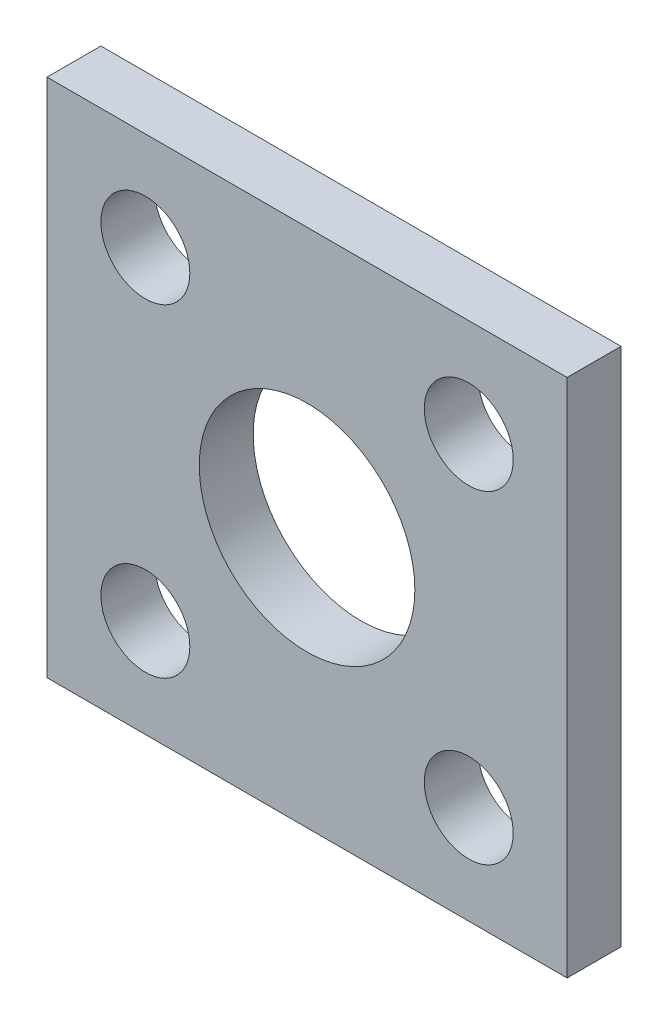
SolidWorks part; units mm, degrees
material "Acrylic (Medium-high impact)"
ref_plane "Front Plane" through (0, 0, 0) normal (0, 0, 1) x (1, 0, 0)
ref_plane "Top Plane" through (0, 0, 0) normal (0, 1, 0) x (1, 0, 0)
ref_plane "Right Plane" through (0, 0, 0) normal (1, 0, 0) x (0, 0, -1)
sketch "Sketch1" plane through (0, 0, 0) normal (0, 0, 1) x (1, 0, 0)
  line L0 (39.125, 39.125) -> (9.125, 9.125) construction
  line L1 (0, 0) -> (48.25, 0)
  line L2 (0, 0) -> (0, 48.25)
  line L3 (0, 48.25) -> (48.25, 48.25)
  line L4 (48.25, 0) -> (48.25, 48.25)
  line L5 (9.125, 9.125) -> (39.125, 9.125) construction
  line L6 (9.125, 9.125) -> (9.125, 39.125) construction
  line L7 (9.125, 39.125) -> (39.125, 39.125) construction
  line L8 (39.125, 9.125) -> (39.125, 39.125) construction
  line L9 (5, 9.125) -> (0, 9.125) construction
  line L10 (34.8959, 1.8) -> (30.6668, 9.125)
  line L11 (17.5832, 9.125) -> (13.3541, 16.45)
  line L12 (13.3541, 16.45) -> (4.8959, 16.45)
  line L13 (4.8959, 16.45) -> (0.6668, 9.125)
  line L14 (0.6668, 9.125) -> (4.8959, 1.8)
  line L15 (4.8959, 1.8) -> (13.3541, 1.8)
  line L16 (13.3541, 1.8) -> (17.5832, 9.125)
  line L17 (43.3541, 1.8) -> (34.8959, 1.8)
  line L18 (47.5832, 9.125) -> (43.3541, 1.8)
  line L19 (43.3541, 16.45) -> (47.5832, 9.125)
  line L20 (9.125, 24.125) -> (0, 24.125) construction
  line L21 (24.125, 9.125) -> (24.125, 0) construction
  line L22 (34.8959, 16.45) -> (43.3541, 16.45)
  line L23 (30.6668, 9.125) -> (34.8959, 16.45)
  line L24 (43.3541, 31.8) -> (47.5832, 39.125)
  line L25 (47.5832, 39.125) -> (43.3541, 46.45)
  line L26 (43.3541, 46.45) -> (34.8959, 46.45)
  line L27 (34.8959, 46.45) -> (30.6668, 39.125)
  line L28 (30.6668, 39.125) -> (34.8959, 31.8)
  line L29 (34.8959, 31.8) -> (43.3541, 31.8)
  line L30 (4.8959, 31.8) -> (0.6668, 39.125)
  line L31 (0.6668, 39.125) -> (4.8959, 46.45)
  line L32 (4.8959, 46.45) -> (13.3541, 46.45)
  line L33 (13.3541, 46.45) -> (17.5832, 39.125)
  line L34 (17.5832, 39.125) -> (13.3541, 31.8)
  line L35 (13.3541, 31.8) -> (4.8959, 31.8)
  circle A0 centre (9.125, 9.125) radius 4.125
  circle A1 centre (9.125, 9.125) radius 7.325 construction
  circle A2 centre (39.125, 9.125) radius 4.125
  circle A3 centre (39.125, 39.125) radius 4.125
  circle A4 centre (24.125, 24.125) radius 10
  circle A5 centre (9.125, 39.125) radius 4.125
  point P47 (24.125, 39.125)
  dimension "D2" = 8.25
  dimension "D3" = 5
  dimension "D4" = 20
  dimension "D1" = 30
  dimension "D5" = 14.65
extrude "Boss-Extrude1" add sketch "Sketch1" along normal blind 5 contours L35 L34 L33 L32 L31 L30 A5 | L15 L16 L11 L12 L13 L14 A0 | L23 L10 L17 L18 L19 L22 A2 | L28 L29 L24 L25 L26 L27 A3 | L1 L4 L3 L2 A4 L10 L23 L22 L19 L18 L17 L16 L15 L14 L13 L12 L11 L29 L28 L27 L26 L25 L24 L34 L35 L30 L31 L32 L33
